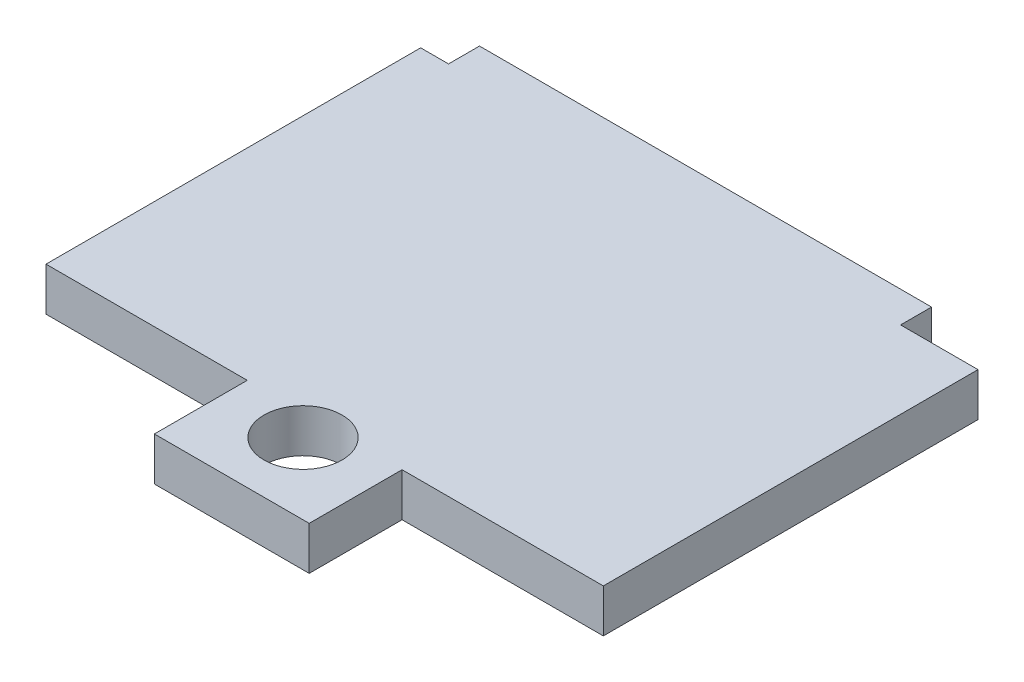
SolidWorks part; units mm, degrees
ref_plane "Front Plane" through (0, 0, 0) normal (0, 0, 1) x (1, 0, 0)
ref_plane "Top Plane" through (0, 0, 0) normal (0, 1, 0) x (1, 0, 0)
ref_plane "Right Plane" through (0, 0, 0) normal (1, 0, 0) x (0, 0, -1)
sketch "Sketch1" plane through (0, 0, 0) normal (0, 1, 0) x (1, 0, 0)
  line L0 (0, 15.367) -> (0, 0)
  line L1 (0, 0) -> (8.255, 0)
  line L2 (8.255, 0) -> (8.255, -3.81)
  line L3 (8.255, -3.81) -> (14.605, -3.81)
  line L4 (14.605, -3.81) -> (14.605, 0)
  line L5 (14.605, 0) -> (22.86, 0)
  line L6 (22.86, 0) -> (22.86, 15.367)
  line L8 (0, 15.367) -> (1.143, 15.367)
  line L9 (1.143, 15.367) -> (1.143, 16.637)
  line L10 (1.143, 16.637) -> (19.685, 16.637)
  line L11 (19.685, 16.637) -> (19.685, 15.367)
  line L12 (19.685, 15.367) -> (22.86, 15.367)
  dimension "D1" = 18.542
  dimension "D2" = 22.86
  dimension "D3" = 1.143
  dimension "D4" = 15.367
  dimension "D5" = 1.27
  dimension "D6" = 3.81
  dimension "D7" = 6.35
  dimension "D8" = 8.255
extrude "Boss-Extrude1" add sketch "Sketch1" along normal blind 1.778
hole_wizard "M3 Clearance Hole1" positions "Sketch2" profile "Sketch3" hole size "M3" standard "ANSI Metric" end condition through all
sketch "Sketch2" plane through (0, 1.778, 0) normal (0, 1, 0) x (1, 0, 0)
  line L0 (8.255, -3.81) -> (14.605, -3.81) construction
  line L1 (23.2514, 2.0338) -> (23.2514, -3.81) construction
  line L2 (12.3825, 2.0338) -> (23.495, 2.0338) construction
  point P0 (11.43, -0.8881)
  point P5 (11.43, -3.81)
  point P13 (23.2514, -0.8881)
sketch "Sketch3" plane through (11.43, 1.778, 0.8881) normal (1, 0, 0) x (0, 0, 1)
  line L0 (0, 0) -> (0, 1.778)
  line L1 (0, 1.778) -> (1.6, 1.778)
  line L2 (1.6, 1.778) -> (1.6, 0)
  line L5 (1.6, 0) -> (0, 0)
  line L11 (0, -6.35) -> (0, 107.95) construction
  dimension "Thru Hole Dia." = 3.2
  dimension "Thru Hole Depth" = 1.778
sketch "Sketch4" plane through (0, 0, 0) normal (0, -1, 0) x (1, 0, 0)
  line L1 (15.24, -4.3028) -> (17.78, -4.3028)
  line L2 (15.24, -4.3028) -> (15.24, -13.4468)
  line L3 (15.24, -13.4468) -> (17.78, -13.4468)
  line L4 (17.78, -4.3028) -> (17.78, -13.4468)
  line L5 (0, -4.3028) -> (2.54, -4.3028)
  line L6 (0, -4.3028) -> (0, -13.4468)
  line L7 (0, -13.4468) -> (2.54, -13.4468)
  line L8 (2.54, -4.3028) -> (2.54, -13.4468)
  line L9 (22.86, 0) -> (22.86, -15.367) construction
  line L10 (-0.635, -12.8914) -> (23.495, -12.8914) construction
  dimension "D1" = 9.144
  dimension "D2" = 2.54
  dimension "D3" = 12.7
  dimension "D4" = 5.08
  dimension "D5" = 0.5554
extrude "Boss-Extrude2" add sketch "Sketch4" along normal blind 0.889
sketch "Sketch5" plane through (0, 0, 0) normal (0, -1, 0) x (1, 0, 0)
  text T0 "<b>35</b>"
extrude "Cut-Extrude1" cut sketch "Sketch5" against normal blind 0.508
